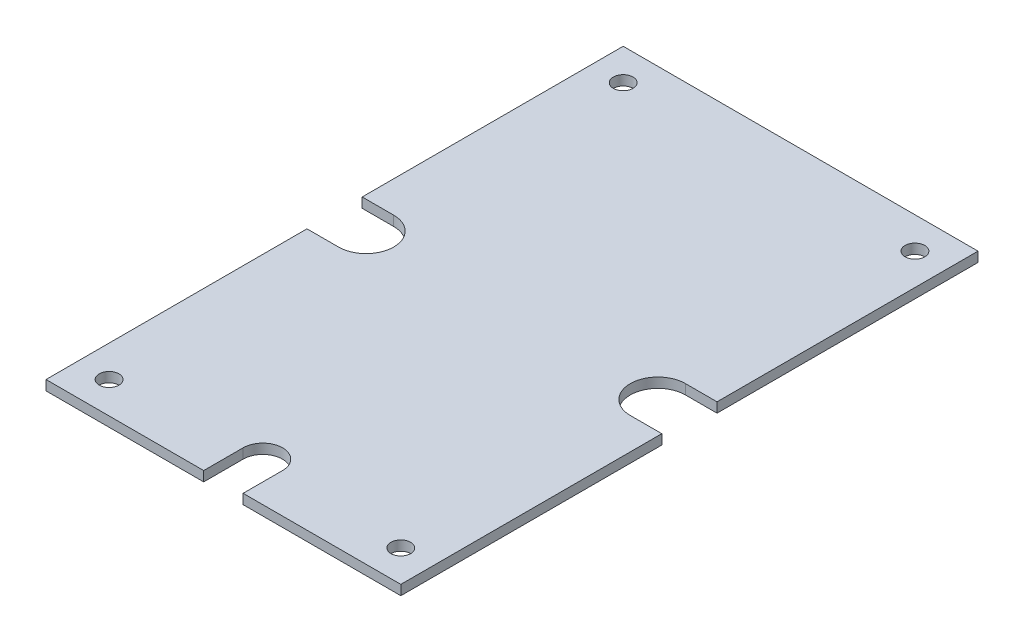
SolidWorks part; units mm, degrees
ref_plane "Front Plane" through (0, 0, 0) normal (0, 0, 1) x (1, 0, 0)
ref_plane "Top Plane" through (0, 0, 0) normal (0, 1, 0) x (1, 0, 0)
ref_plane "Right Plane" through (0, 0, 0) normal (1, 0, 0) x (0, 0, -1)
sketch "Sketch1" plane through (0, 0, 0) normal (0, 1, 0) x (1, 0, 0)
  line L1 (0, 0) -> (57.15, 0)
  line L2 (0, 0) -> (0, 92.964)
  line L3 (0, 92.964) -> (57.15, 92.964)
  line L4 (57.15, 0) -> (57.15, 92.964)
  dimension "D1" = 57.15
  dimension "D2" = 92.964
extrude "Boss-Extrude1" add sketch "Sketch1" along normal blind 1.5875
sketch "Sketch2" plane through (0, 1.5875, 0) normal (0, 1, 0) x (1, 0, 0)
  line L0 (5.08, 46.482) -> (0, 46.482) construction
  line L1 (5.08, 5.08) -> (52.07, 5.08) construction
  line L2 (5.08, 5.08) -> (5.08, 87.884) construction
  line L3 (5.08, 87.884) -> (52.07, 87.884) construction
  line L4 (52.07, 5.08) -> (52.07, 87.884) construction
  line L5 (0, 92.964) -> (0, 0) construction
  line L6 (52.07, 46.482) -> (57.15, 46.482) construction
  line L7 (57.15, 0) -> (57.15, 92.964) construction
  line L8 (28.575, 87.884) -> (28.575, 92.964) construction
  line L9 (57.15, 92.964) -> (0, 92.964) construction
  line L10 (28.575, 5.08) -> (28.575, 0) construction
  line L11 (0, 0) -> (57.15, 0) construction
  circle A0 centre (5.08, 87.884) radius 1.5875
  circle A1 centre (52.07, 87.884) radius 1.5875
  circle A2 centre (5.08, 5.08) radius 1.5875
  circle A3 centre (52.07, 5.08) radius 1.5875
  dimension "D3" = 3.175
  dimension "D1" = 46.99
  dimension "D2" = 82.804
extrude "Cut-Extrude1" cut sketch "Sketch2" against normal through all contours A0 | A1 | A2 | A3
sketch "Sketch3" plane through (0, 1.5875, 0) normal (0, 1, 0) x (1, 0, 0)
  line L2 (57.15, 92.964) -> (0, 92.964) construction
  line L3 (57.15, 0) -> (57.15, 92.964) construction
  line L4 (52.07, 42.037) -> (57.15, 42.037)
  line L5 (57.15, 42.037) -> (57.15, 50.927)
  line L6 (57.15, 50.927) -> (52.07, 50.927)
  line L7 (28.575, 0) -> (28.575, 92.964) construction
  line L8 (0, 0) -> (57.15, 0) construction
  line L9 (0, 50.927) -> (5.08, 50.927)
  line L10 (0, 42.037) -> (0, 50.927)
  line L11 (5.08, 42.037) -> (0, 42.037)
  line L12 (57.15, 46.482) -> (0, 46.482) construction
  circle A1 centre (52.07, 46.482) radius 4.445
  circle A2 centre (5.08, 46.482) radius 4.445
  line M5 (0, 92.964) -> (0, 0)
  line M7 (57.15, 0) -> (57.15, 92.964)
  dimension "D3" = 8.89
  dimension "D2" = 5.08
extrude "Cut-Extrude2" cut sketch "Sketch3" against normal through all contours A1 L4 L6 M7 | A1 | A2 | L11 A2 L9 M5
sketch "Sketch4" plane through (0, 1.5875, 0) normal (0, 1, 0) x (1, 0, 0)
  line L0 (0, 0) -> (57.15, 0) construction
  line L1 (31.75, 6.35) -> (31.75, 0)
  line L2 (31.75, 0) -> (25.4, 0)
  line L3 (25.4, 0) -> (25.4, 6.35)
  line L4 (28.575, 92.964) -> (28.575, 0) construction
  line L5 (57.15, 92.964) -> (0, 92.964) construction
  circle A0 centre (28.575, 6.35) radius 3.175
  point P12 (0, 0)
  line M15 (0, 0) -> (57.15, 0)
  dimension "D1" = 6.35
  dimension "D2" = 6.35
extrude "Cut-Extrude3" cut sketch "Sketch4" against normal up to next contours A0 L4 | L4 A0 | L4 A0 L3 M15 | A0 L4 L2 L1
